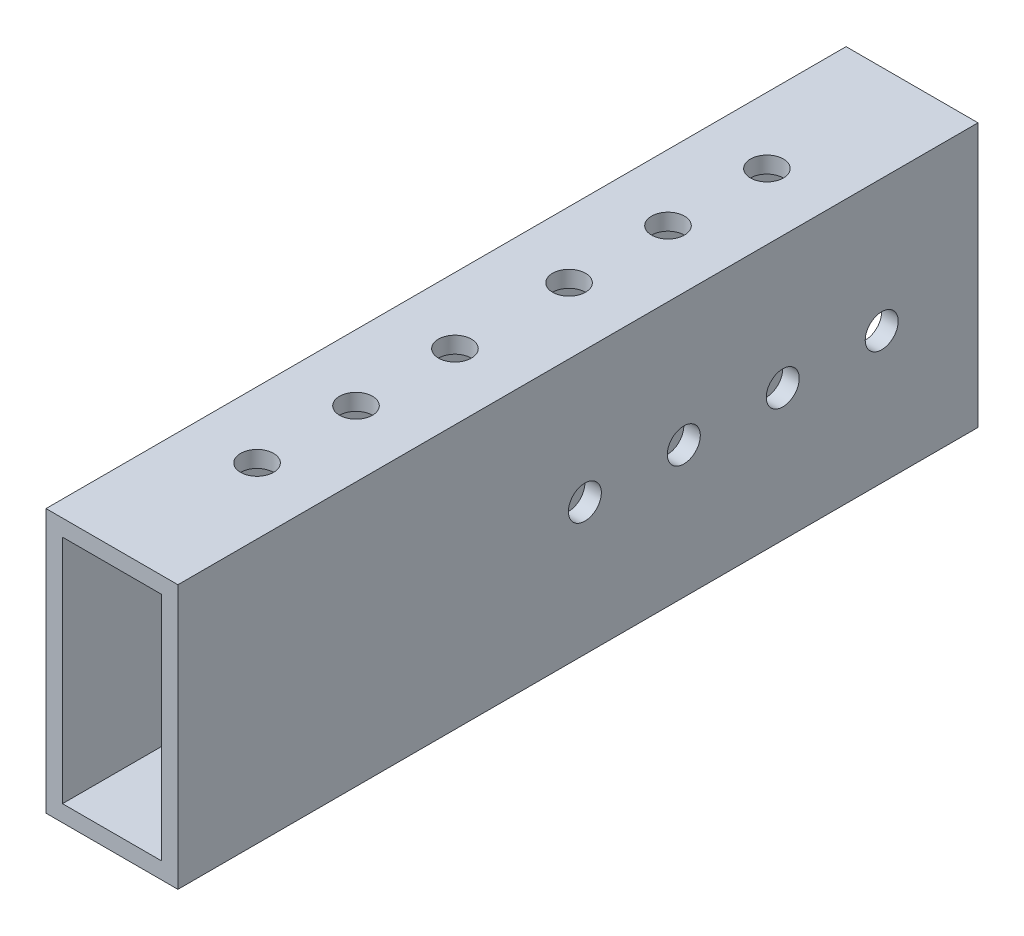
SolidWorks part; units mm, degrees
ref_plane "Front Plane" through (0, 0, 0) normal (0, 0, 1) x (1, 0, 0)
ref_plane "Top Plane" through (0, 0, 0) normal (0, 1, 0) x (1, 0, 0)
ref_plane "Right Plane" through (0, 0, 0) normal (1, 0, 0) x (0, 0, -1)
sketch "Sketch1" plane through (0, 0, 0) normal (0, 0, 1) x (1, 0, 0)
  line L0 (3.175, 47.625) -> (22.225, 47.625)
  line L1 (0, 0) -> (25.4, 0)
  line L2 (0, 0) -> (0, 50.8)
  line L3 (0, 50.8) -> (25.4, 50.8)
  line L4 (25.4, 0) -> (25.4, 50.8)
  line L5 (22.225, 3.175) -> (22.225, 47.625)
  line L6 (3.175, 3.175) -> (22.225, 3.175)
  line L7 (3.175, 3.175) -> (3.175, 47.625)
  dimension "D1" = 50.8
  dimension "D2" = 25.4
  dimension "D3" = 3.175
extrude "Boss-Extrude1" add sketch "Sketch1" along normal blind 154.051
sketch "Sketch2" plane through (0, 50.8, 0) normal (0, 1, 0) x (1, 0, 0)
  line L0 (25.4, -154.051) -> (0, -154.051) construction
  line L1 (0, -154.051) -> (0, 0) construction
  line L3 (0, -77.0255) -> (25.4, -77.0255) construction
  line L4 (25.4, -154.051) -> (25.4, 0) construction
  circle A0 centre (12.7, -126.111) radius 3.175
  circle A1 centre (12.7, -107.061) radius 3.175
  circle A2 centre (12.7, -88.011) radius 3.175
  circle A3 centre (12.7, -27.94) radius 3.175
  circle A4 centre (12.7, -46.99) radius 3.175
  circle A5 centre (12.7, -66.04) radius 3.175
  dimension "D3" = 6.35
  dimension "D4" = 6.35
  dimension "D5" = 6.35
  dimension "D1" = 19.05
  dimension "D2" = 19.05
  dimension "D6" = 27.94
  dimension "D7" = 12.7
  dimension "D8" = 12.7
  dimension "D9" = 12.7
extrude "Cut-Extrude1" cut sketch "Sketch2" against normal through all
sketch "Sketch3" plane through (25.4, 0, 0) normal (1, 0, 0) x (0, 0, -1)
  line L0 (-154.051, 50.8) -> (0, 50.8) construction
  line L1 (0, 0) -> (0, 50.8) construction
  circle A0 centre (-18.542, 25.4) radius 3.175
  circle A1 centre (-37.592, 25.4) radius 3.175
  circle A2 centre (-56.642, 25.4) radius 3.175
  circle A3 centre (-75.692, 25.4) radius 3.175
  point P14 (-25.2535, 31.5482)
  dimension "D1" = 6.35
  dimension "D2" = 6.35
  dimension "D3" = 6.35
  dimension "D4" = 6.35
  dimension "D5" = 25.4
  dimension "D6" = 25.4
  dimension "D7" = 25.4
  dimension "D8" = 25.4
  dimension "D9" = 18.542
  dimension "D10" = 19.05
  dimension "D11" = 19.05
  dimension "D12" = 19.05
extrude "Cut-Extrude2" cut sketch "Sketch3" against normal through all
